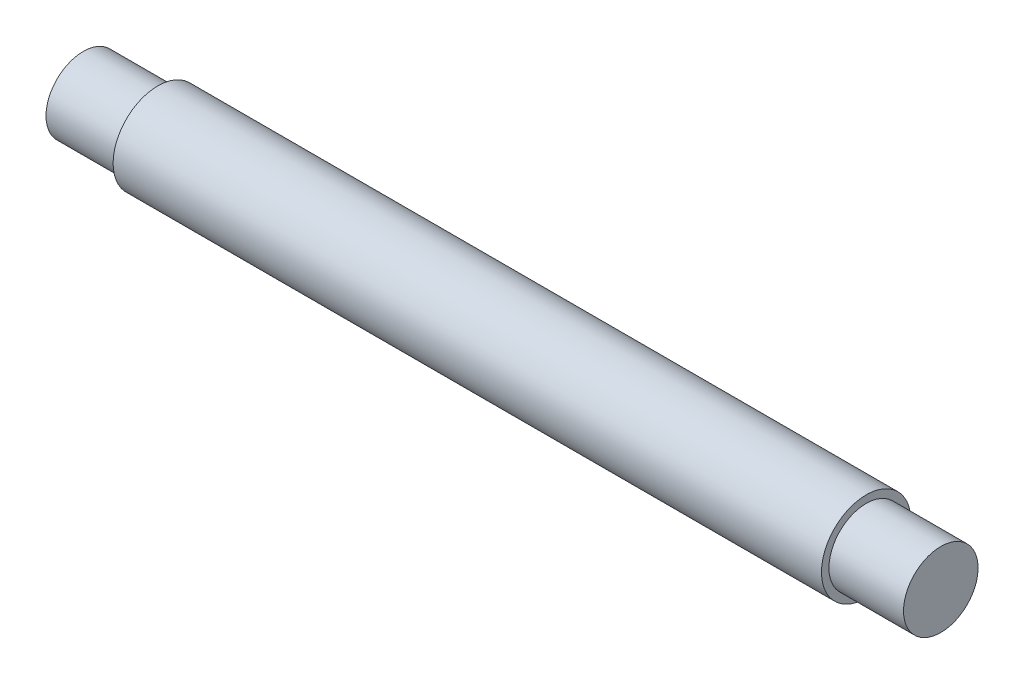
SolidWorks part; units mm, degrees
ref_plane "Ön Düzlem" through (0, 0, 0) normal (0, 0, 1) x (1, 0, 0)
ref_plane "Üst Düzlem" through (0, 0, 0) normal (0, 1, 0) x (1, 0, 0)
ref_plane "Sağ Düzlem" through (0, 0, 0) normal (1, 0, 0) x (0, 0, -1)
sketch "Çizim4" plane through (0, 0, 0) normal (0, 1, 0) x (1, 0, 0)
  line L0 (0, 0) -> (115, 0) construction
  line L1 (115, 0) -> (115, 5)
  line L2 (115, 5) -> (105, 5)
  line L3 (105, 5) -> (105, 6)
  line L4 (105, 6) -> (10, 6)
  line L5 (10, 6) -> (10, 5)
  line L6 (10, 5) -> (0, 5)
  line L7 (0, 5) -> (0, 0)
  line L8 (0, 0) -> (115, 0)
  dimension "D1" = 115
  dimension "D2" = 10
  dimension "D3" = 12
  dimension "D4" = 5
  dimension "D5" = 5
revolve "Döndür1" add sketch "Çizim4" angle 360 about L0
cosmetic thread "Kozmetik Diş Açma1" parameters "D2"=8.891
cosmetic thread "Kozmetik Diş Açma2" parameters "D2"=8.344
